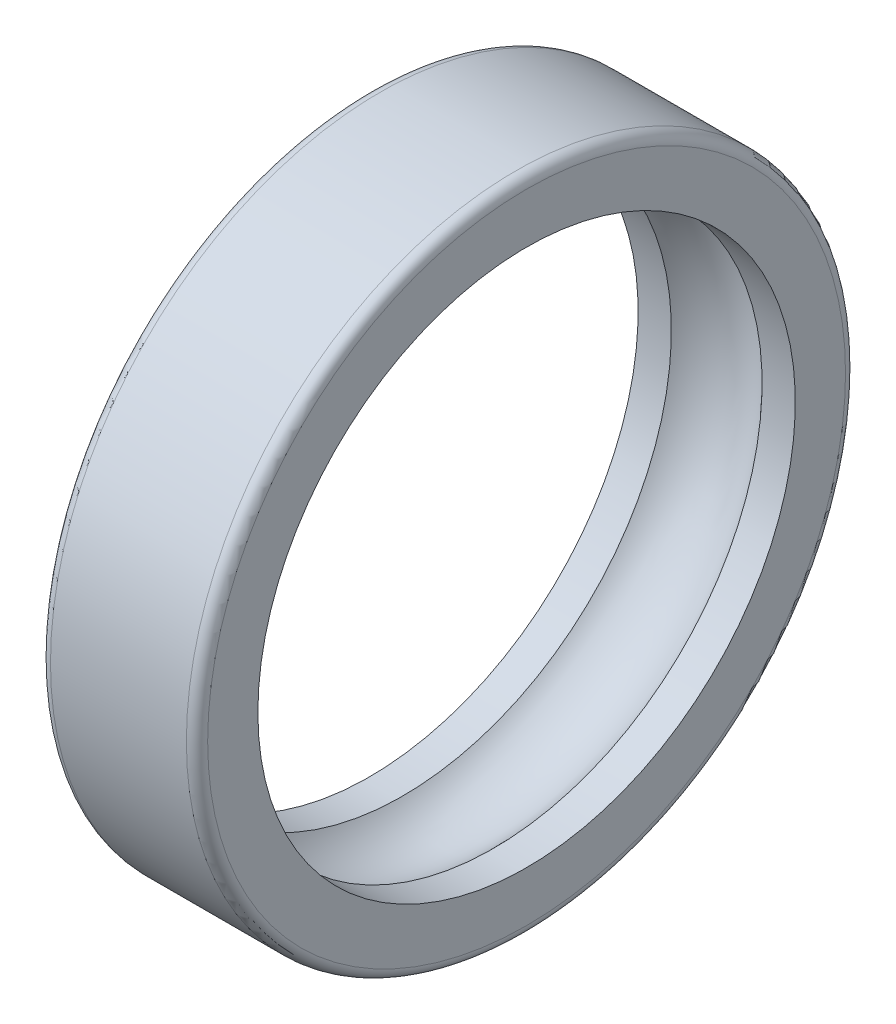
SolidWorks part; units mm, degrees
ref_plane "Ön Düzlem" through (0, 0, 0) normal (0, 0, 1) x (1, 0, 0)
ref_plane "Üst Düzlem" through (0, 0, 0) normal (0, 1, 0) x (1, 0, 0)
ref_plane "Sağ Düzlem" through (0, 0, 0) normal (1, 0, 0) x (0, 0, -1)
sketch "Çizim1" plane through (0, 0, 0) normal (0, 0, 1) x (1, 0, 0)
  line L0 (-12.3345, 0) -> (25.4331, 0) construction
  line L1 (0, 53) -> (0, 0) construction
  line L2 (-15.5, 53) -> (-8.9443, 53)
  line L3 (-15.5, 53) -> (-15.5, 65)
  line L4 (-15.5, 65) -> (15.5, 65)
  line L5 (15.5, 53) -> (15.5, 65)
  line L6 (-15.5, 53) -> (15.5, 65) construction
  line L7 (-15.5, 65) -> (15.5, 53) construction
  line L8 (0, 0) -> (0, 53) construction
  line L9 (8.9443, 53) -> (15.5, 53)
  arc A0 (-8.9443, 53) -> (8.9443, 53) centre (0, 45) cw
  point P3 (0, 59)
  dimension "D5" = 12
  dimension "D1" = 31
  dimension "D2" = 53
  dimension "D3" = 65
  dimension "D4" = 8
revolve "Döndür1" add sketch "Çizim1" angle 360 about L0
fillet "Radyus1" radius 2.1 2 edges at (15.5, 0, 65) (-15.5, 0, 65)
